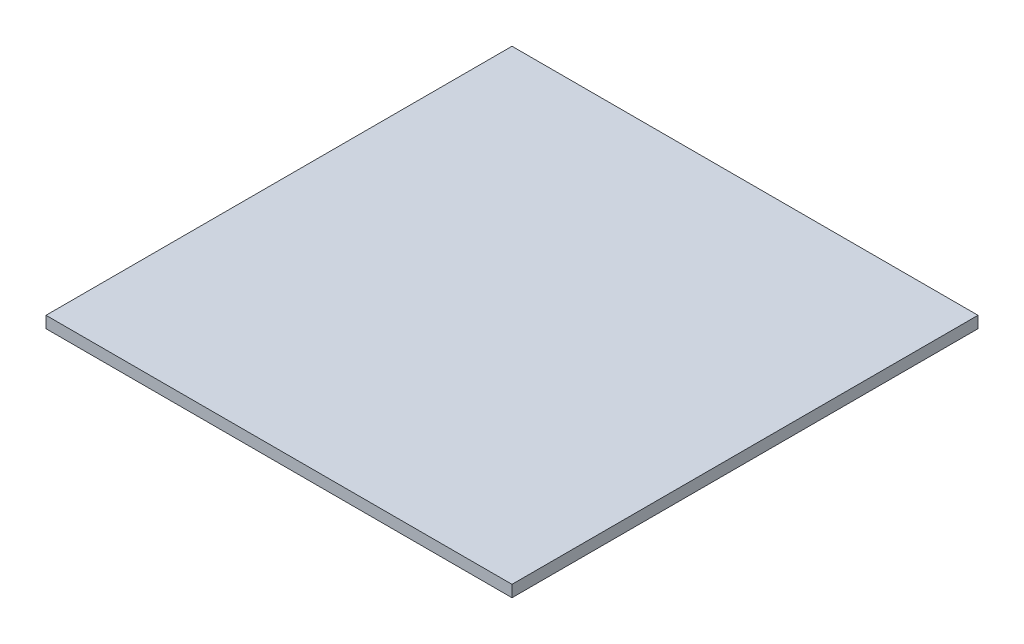
SolidWorks part; units mm, degrees
material "Balsa"
ref_plane "Plano frontal" through (0, 0, 0) normal (0, 0, 1) x (1, 0, 0)
ref_plane "Plano superior" through (0, 0, 0) normal (0, 1, 0) x (1, 0, 0)
ref_plane "Plano direito" through (0, 0, 0) normal (1, 0, 0) x (0, 0, -1)
sketch "Esboço1" plane through (0, 0, 0) normal (0, 1, 0) x (1, 0, 0)
  line L1 (-300, -300) -> (300, -300)
  line L2 (-300, -300) -> (-300, 300)
  line L3 (-300, 300) -> (300, 300)
  line L4 (300, -300) -> (300, 300)
  line L5 (-300, -300) -> (300, 300) construction
  line L6 (-300, 300) -> (300, -300) construction
  point P0 (0, 0)
  dimension "D1" = 600
  dimension "D2" = 600
extrude "Ressalto-extrusão1" add sketch "Esboço1" along normal blind 15
ref_plane "Plane1" through (0, 0, 0) normal (0, 0, 1) x (1, 0, 0)
